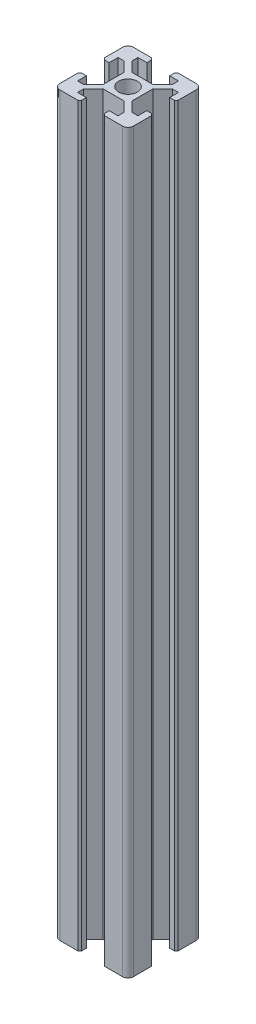
SolidWorks part; units mm, degrees
material "1060 合金"
ref_plane "前视" through (0, 0, 0) normal (0, 0, 1) x (1, 0, 0)
ref_plane "上视" through (0, 0, 0) normal (0, 1, 0) x (1, 0, 0)
ref_plane "右视" through (0, 0, 0) normal (1, 0, 0) x (0, 0, -1)
sketch "草图1" plane through (0, 0, 0) normal (0, 1, 0) x (1, 0, 0)
  line L0 (13.9, 12.8393) -> (13.9, 7.1607)
  line L5 (12.8393, 6.1) -> (7.1607, 6.1)
  line L6 (0, 20) -> (20, 0) construction
  line L7 (20, 20) -> (0, 0) construction
  line L8 (4.5, 18.2) -> (6.9, 18.2)
  line L9 (18.2, 4.5) -> (18.2, 6.9)
  line L10 (4.5, 1.8) -> (6.9, 1.8)
  line L11 (1.8, 4.5) -> (1.8, 6.9)
  line L12 (3.4393, 15.5) -> (6.1, 12.8393)
  line L16 (1.5, 0) -> (6.4, 0)
  line L17 (4.5, 16.5607) -> (7.1607, 13.9)
  line L18 (15.5, 16.5607) -> (12.8393, 13.9)
  line L19 (16.5607, 15.5) -> (13.9, 12.8393)
  line L21 (0, 13.6) -> (0.5, 13.1)
  line L22 (19.4697, 20.5303) -> (-0.5303, 0.5303) construction
  line L23 (20.5303, 19.4697) -> (0.5303, -0.5303) construction
  line L24 (13.9, 7.1607) -> (16.5607, 4.5)
  line L25 (12.8393, 6.1) -> (15.5, 3.4393)
  line L28 (7.1607, 6.1) -> (4.5, 3.4393)
  line L30 (6.1, 7.1607) -> (3.4393, 4.5)
  line L31 (0.5, 6.9) -> (1.8, 6.9)
  line L32 (0.5, 13.1) -> (1.8, 13.1)
  line L33 (6.9, 19.5) -> (6.9, 18.2)
  line L34 (13.1, 19.5) -> (13.1, 18.2)
  line L35 (6.9, 1.8) -> (6.9, 0.5)
  line L36 (6.1, 7.1607) -> (6.1, 12.8393)
  line L37 (13.1, 1.8) -> (13.1, 0.5)
  line L38 (7.1607, 13.9) -> (12.8393, 13.9)
  line L39 (1.8, 13.1) -> (1.8, 15.5)
  line L40 (0, 1.5) -> (0, 6.4)
  line L41 (18.2, 13.1) -> (19.5, 13.1)
  line L42 (1.8, 4.5) -> (3.4393, 4.5)
  line L44 (18.2, 6.9) -> (19.5, 6.9)
  line L46 (13.1, 1.8) -> (15.5, 1.8)
  line L51 (13.1, 18.2) -> (15.5, 18.2)
  line L54 (18.2, 13.1) -> (18.2, 15.5)
  line L56 (4.5, 1.8) -> (4.5, 3.4393)
  line L57 (1.5, 20) -> (6.4, 20)
  line L58 (0, 18.5) -> (0, 13.6)
  line L59 (1.8, 15.5) -> (3.4393, 15.5)
  line L60 (4.5, 18.2) -> (4.5, 16.5607)
  line L61 (18.5, 20) -> (13.6, 20)
  line L62 (20, 18.5) -> (20, 13.6)
  line L63 (18.2, 15.5) -> (16.5607, 15.5)
  line L64 (15.5, 18.2) -> (15.5, 16.5607)
  line L65 (18.5, 0) -> (13.6, 0)
  line L66 (20, 1.5) -> (20, 6.4)
  line L67 (18.2, 4.5) -> (16.5607, 4.5)
  line L68 (15.5, 1.8) -> (15.5, 3.4393)
  line L69 (0, 6.4) -> (0.5, 6.9)
  line L70 (6.4, 0) -> (6.9, 0.5)
  line L72 (13.6, 0) -> (13.1, 0.5)
  line L73 (20, 6.4) -> (19.5, 6.9)
  line L75 (20, 13.6) -> (19.5, 13.1)
  line L76 (13.6, 20) -> (13.1, 19.5)
  line L77 (6.4, 20) -> (6.9, 19.5)
  circle A0 centre (10, 10) radius 2.55
  arc A1 (18.5, 20) -> (20, 18.5) centre (18.5, 18.5) cw
  arc A2 (0, 18.5) -> (1.5, 20) centre (1.5, 18.5) cw
  arc A3 (0, 1.5) -> (1.5, 0) centre (1.5, 1.5) ccw
  arc A4 (20, 1.5) -> (18.5, 0) centre (18.5, 1.5) cw
  dimension "D3" = 5.1
  dimension "D5" = 1.5
  dimension "D6" = 1.5
  dimension "D7" = 1.5
  dimension "D8" = 1.5
  dimension "D1" = 20
  dimension "D2" = 20
extrude "凸台-拉伸2" add sketch "草图1" along normal blind 200 contours L51 L64 L18 L38 L17 L60 L8 L33 L77 L57 A2 L58 L21 L32 L39 L59 L12 L36 L30 L42 L11 L31 L69 L40 A3 L16 L70 L35 L10 L56 L28 L5 L25 L68 L46 L37 L72 L65 A4 L66 L73 L44 L9 L67 L24 L0 L19 L63 L54 L41 L75 L62 A1 L61 L76 L34
sketch "草图4" plane through (0, 0, 0) normal (0, -1, 0) x (1, 0, 0)
  circle A4 centre (10, -10) radius 2.55
  dimension "D1" = 5.1
extrude "切除-拉伸2" cut sketch "草图4" against normal through all
